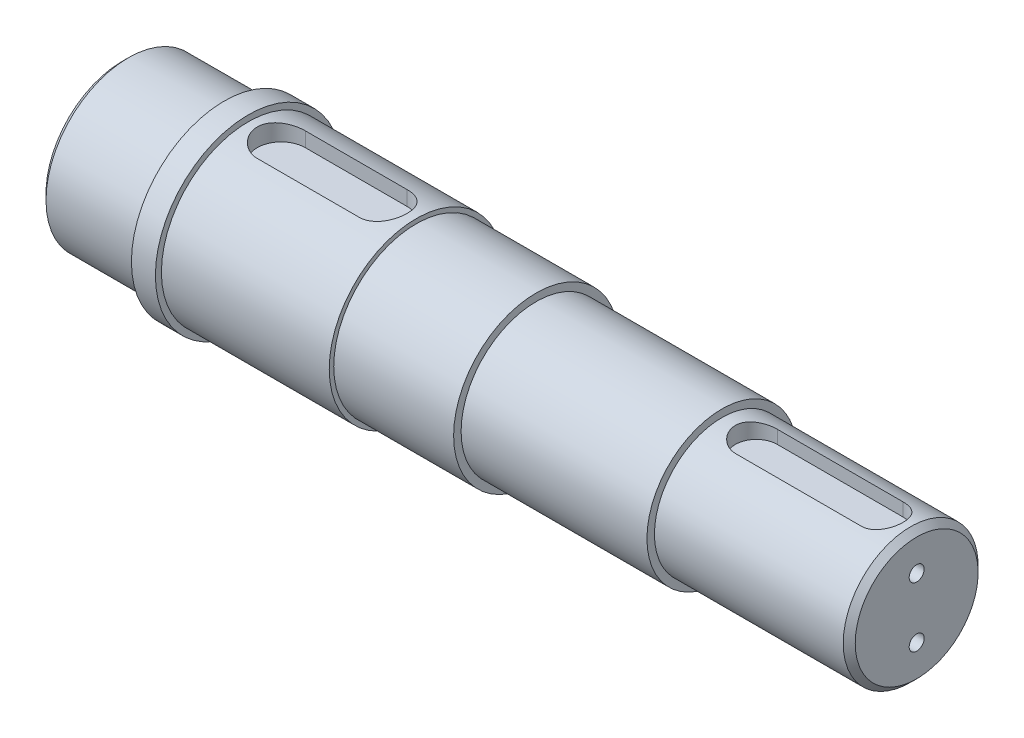
SolidWorks part; units mm, degrees
ref_plane "前视基准面" through (0, 0, 0) normal (0, 0, 1) x (1, 0, 0)
ref_plane "上视基准面" through (0, 0, 0) normal (0, 1, 0) x (1, 0, 0)
ref_plane "右视基准面" through (0, 0, 0) normal (1, 0, 0) x (0, 0, -1)
sketch "草图1" plane through (0, 0, 0) normal (0, 0, 1) x (1, 0, 0)
  line L0 (-104.077, 0) -> (202.332, 0) construction
  line L1 (-76.9911, 0) -> (188.0089, 0)
  line L2 (188.0089, 0) -> (188.0089, 22.5)
  line L3 (188.0089, 22.5) -> (123.0089, 22.5)
  line L4 (123.0089, 22.5) -> (123.0089, 25)
  line L5 (123.0089, 25) -> (61.0089, 25)
  line L6 (61.0089, 25) -> (61.0089, 27.5)
  line L7 (61.0089, 27.5) -> (21.0089, 27.5)
  line L8 (21.0089, 27.5) -> (21.0089, 29)
  line L9 (21.0089, 29) -> (-34.9911, 29)
  line L10 (-34.9911, 29) -> (-34.9911, 31)
  line L11 (-34.9911, 31) -> (-42.9911, 31)
  line L12 (-42.9911, 31) -> (-42.9911, 27.5)
  line L13 (-76.9911, 27.5) -> (-42.9911, 27.5)
  line L16 (-76.9911, 27.5) -> (-76.9911, 0)
  dimension "D1" = 22.5
  dimension "D2" = 25
  dimension "D3" = 2.5
  dimension "D4" = 29
  dimension "D5" = 65
  dimension "D6" = 167
  dimension "D7" = 127
  dimension "D8" = 56
  dimension "D9" = 31
  dimension "D10" = 8
revolve "旋转1" add sketch "草图1" angle 360 about L0
ref_plane "基准面1" through (0, 29, 0) normal (0, 1, 0) x (-1, 0, 0)
sketch "草图2" plane through (0, 29, 0) normal (0, 1, 0) x (-1, 0, 0)
  line L0 (-21.0089, 0) -> (34.9911, 0) construction
  line L3 (-21.0089, 29) -> (-21.0089, -29) construction
  line L4 (34.9911, 31) -> (34.9911, -31) construction
  line L6 (23.9911, -8) -> (-10.0089, -8)
  line L8 (23.9911, 8) -> (-10.0089, 8)
  line L10 (23.9911, -8) -> (-10.0089, 8) construction
  line L11 (23.9911, 8) -> (-10.0089, -8) construction
  arc A0 (-10.0089, 8) -> (-10.0089, -8) centre (-10.0089, 0) ccw
  arc A1 (23.9911, 8) -> (23.9911, -8) centre (23.9911, 0) cw
  point P6 (6.9911, 0)
  dimension "D1" = 34
  dimension "D2" = 16
extrude "切除-拉伸1" cut sketch "草图2" against normal blind 6
ref_plane "基准面2" through (0, 22.5, 0) normal (0, 1, 0) x (-1, 0, 0)
sketch "草图3" plane through (0, 22.5, 0) normal (0, 1, 0) x (-1, 0, 0)
  line L0 (-188.0089, 0) -> (76.9911, 0) construction
  line L1 (-188.0089, 22.5) -> (-188.0089, -22.5) construction
  line L2 (76.9911, -27.5) -> (76.9911, 27.5) construction
  line L3 (-176.5089, 7) -> (-134.5089, 7)
  line L5 (-176.5089, -7) -> (-134.5089, -7)
  arc A0 (-183.5089, 0) -> (-176.5089, 7) centre (-176.5089, 0) cw
  arc A1 (-183.5089, 0) -> (-176.5089, -7) centre (-176.5089, 0) ccw
  arc A2 (-127.5089, 0) -> (-134.5089, -7) centre (-134.5089, 0) cw
  arc A3 (-127.5089, 0) -> (-134.5089, 7) centre (-134.5089, 0) ccw
extrude "切除-拉伸2" cut sketch "草图3" against normal blind 5.5
chamfer "倒角1" distance 2 angle 45 2 edges at (-76.9911, 0, 27.5) (188.0089, 0, 22.5)
sketch "草图4" plane through (188.0089, 0, 0) normal (1, 0, 0) x (0, 0, -1)
  line L0 (0, 20.5) -> (0, -20.5) construction
  circle A0 centre (0, 0) radius 20.5 construction
hole_wizard "M6 螺纹孔1" positions "草图6" profile "草图5" tap size "M6" standard "GB"
sketch "草图6" plane through (188.0089, 0, 0) normal (1, 0, 0) x (0, 0, -1)
  line L0 (0, 20.5) -> (0, -20.5) construction
  point P0 (0, 10)
  point P3 (0, -10)
  dimension "D1" = 0
  dimension "D2" = 10
  dimension "D3" = 10
  dimension "D4" = 0
sketch "草图5" plane through (188.0089, 10, 0) normal (0, 1, 0) x (0, 0, -1)
  line L0 (0, 0) -> (0, 18.5022)
  line L1 (0, 18.5022) -> (2.5, 17)
  line L2 (2.5, 17) -> (2.5, 0)
  line L5 (2.5, 0) -> (0, 0)
  line L10 (0, 18.5022) -> (-2.5, 17) construction
  line L11 (0, -6.35) -> (0, 107.95) construction
  dimension "螺纹孔钻头直径" = 5
  dimension "螺纹孔钻头深度" = 17
  dimension "导头角度" = 118
cosmetic thread "孔螺蚊线1" parameters "D1"=12, "D2"=6
cosmetic thread "孔螺蚊线2" parameters "D1"=12, "D2"=6
